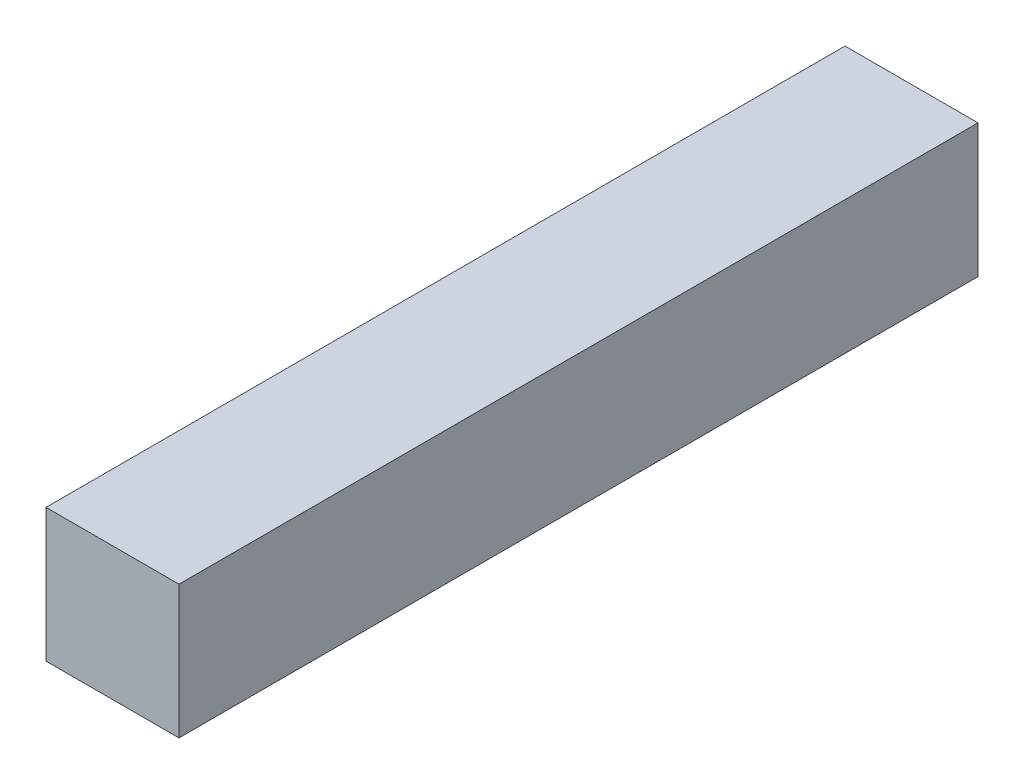
SolidWorks part; units mm, degrees
ref_plane "Front Plane" through (0, 0, 0) normal (0, 0, 1) x (1, 0, 0)
ref_plane "Top Plane" through (0, 0, 0) normal (0, 1, 0) x (1, 0, 0)
ref_plane "Right Plane" through (0, 0, 0) normal (1, 0, 0) x (0, 0, -1)
sketch "Sketch1" plane through (0, 0, 0) normal (0, 0, 1) x (1, 0, 0)
  line L0 (0, 0) -> (-99.881, 0)
  line L1 (-99.881, 0) -> (-99.881, -100)
  line L2 (-99.881, -100) -> (0, -100)
  line L3 (0, -100) -> (0, 0)
extrude "Boss-Extrude1" add sketch "Sketch1" along normal blind 600 contours L3 L0 L1 L2
